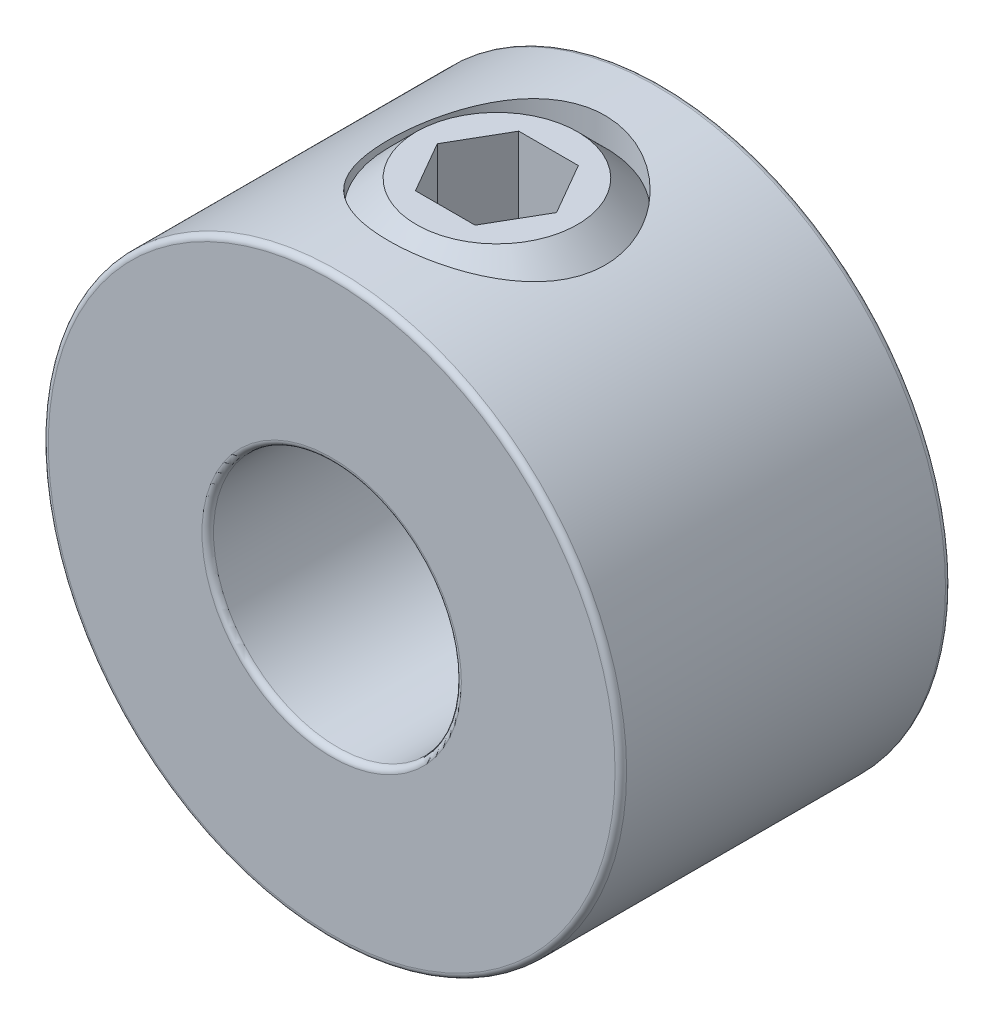
SolidWorks part; units mm, degrees
ref_plane "Front Plane" through (0, 0, 0) normal (0, 0, 1) x (1, 0, 0)
ref_plane "Top Plane" through (0, 0, 0) normal (0, 1, 0) x (1, 0, 0)
ref_plane "Right Plane" through (0, 0, 0) normal (1, 0, 0) x (0, 0, -1)
sketch "Sketch1" plane through (0, 0, 0) normal (0, 0, 1) x (1, 0, 0)
  circle A0 centre (0, 0) radius 5.5562
  circle A1 centre (0, 0) radius 2.3813
  point P4 (5.5562, 0)
  dimension "Bore Dia" = 4.7625
  dimension "OD" = 11.1125
extrude "Extrude1" add sketch "Sketch1" along normal mid plane 6.35
sketch "Sketch2" plane through (41.275, 0, 0) normal (0, -1, 0) x (0, 0, -1)
  line L0 (3.175, -41.275) -> (-3.175, -41.275) construction
  line L1 (-3.175, -35.7188) -> (-3.175, -46.8312) construction
  line L2 (3.175, -46.8312) -> (3.175, -35.7188) construction
  circle A0 centre (0, -41.275) radius 2.0828
  point P7 (0, -43.3578)
  dimension "Set Screw Dia" = 4.1656
extrude "Cut-Extrude1" cut sketch "Sketch2" against normal through all
fillet "Fillet1" radius 0.1111 4 edges at (2.3813, 0, -3.175) (2.3813, 0, 3.175) (5.5562, 0, -3.175) (5.5562, 0, 3.175)
sketch "Sketch3" plane through (0, 0, 0) normal (0, 0, 1) x (1, 0, 0)
  line L0 (-1.5473, 2.3813) -> (-0.6426, 2.3813)
  line L1 (0, 3.0238) -> (-0.6426, 2.3813)
  line L2 (0, 3.0238) -> (0, 5.5563)
  line L3 (0, 5.5563) -> (-1.5473, 5.5563)
  line L4 (-2.0828, 2.9167) -> (-2.0828, 5.0208)
  line L5 (0, 2.3813) -> (0, 0) construction
  line L6 (-2.0828, 2.9167) -> (-2.0828, 2.3813) construction
  line L7 (-2.0828, 2.3813) -> (-1.5473, 2.3813) construction
  line L8 (-2.0828, 5.0208) -> (-2.0828, 5.5563) construction
  line L9 (-1.5473, 2.3813) -> (-2.0828, 2.9167)
  line L10 (-2.0828, 5.0208) -> (-1.5473, 5.5563)
  line L11 (-2.0828, 5.5563) -> (-1.5473, 5.5563) construction
  line L12 (-0.6426, 2.3813) -> (0, 2.3813) construction
  line L13 (0, 2.3813) -> (0, 3.0238) construction
  circle A1 centre (0, 0) radius 2.3813 construction
  dimension "D1" = 0.6426
  dimension "D2" = 0.5355
  dimension "Screw Length" = 3.175
revolve "Revolve1" add sketch "Sketch3" angle 360 about L5
sketch "Sketch4" plane through (3.3734, 5.5562, 0) normal (0, -1, 0) x (0, 0, -1)
  line L1 (0, -2.2278) -> (-0.9922, -2.8006)
  line L2 (-0.9922, -2.8006) -> (-0.9922, -3.9463)
  line L3 (-0.9922, -3.9463) -> (0, -4.5191)
  line L4 (0, -4.5191) -> (0.9922, -3.9463)
  line L5 (0.9922, -3.9463) -> (0.9922, -2.8006)
  line L6 (0.9922, -2.8006) -> (0, -2.2278)
  circle A0 centre (0, -3.3734) radius 0.9922 construction
  circle A1 centre (0, -3.3734) radius 1.1457 construction
  dimension "D1" = 2.2914
  dimension "Hex Size" = 1.9844
extrude "Cut-Extrude2" cut sketch "Sketch4" along normal blind 1.9844
equation "\"D1@Fillet1\" = \"OD@Sketch1\"*.01"
equation "\"D1@Cut-Extrude2\" = \"Hex Size@Sketch4\""
equation "\"D2@Sketch3\" =(\"Set Screw Dia@Sketch2\"-\"D1@Sketch4\")/3.5"
equation "\"D1@Sketch3\" = \"D2@Sketch3\"*1.2"
